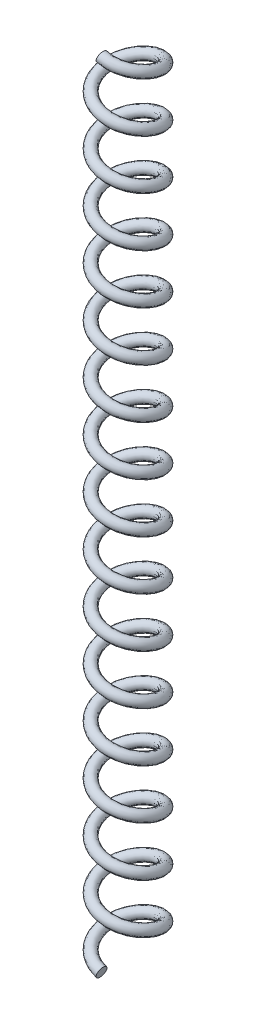
SolidWorks part; units mm, degrees
ref_plane "Front Plane" through (0, 0, 0) normal (0, 0, 1) x (1, 0, 0)
ref_plane "Top Plane" through (0, 0, 0) normal (0, 1, 0) x (1, 0, 0)
ref_plane "Right Plane" through (0, 0, 0) normal (1, 0, 0) x (0, 0, -1)
other "Configuration Table"
sketch "Sketch1" plane through (0, 0, 0) normal (0, 1, 0) x (1, 0, 0)
  circle A0 centre (0, 0) radius 2.5
curve "Coil_Helix" pitch 4.6875 height 75 turns 16
sweep "Coil_Wire" add path "Coil_Helix" circular profile diameter 1 parameters "D3"=1
